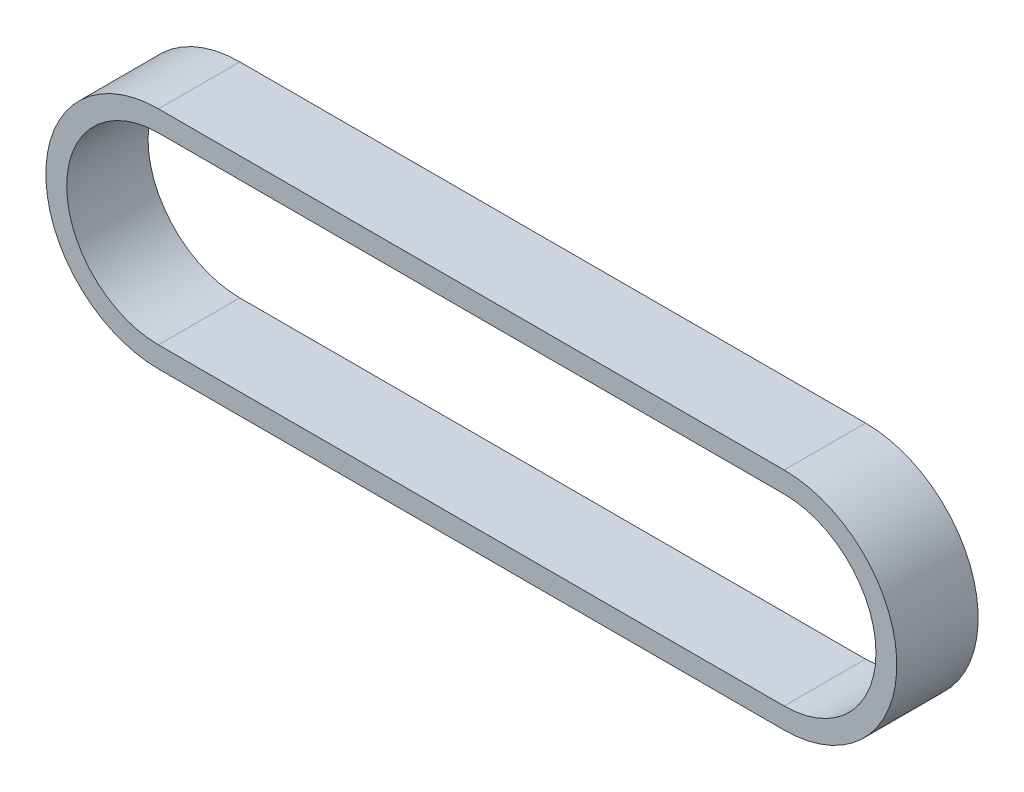
SolidWorks part; units mm, degrees
material "Rubber"
ref_plane "Front Plane" through (0, 0, 0) normal (0, 0, 1) x (1, 0, 0)
ref_plane "Top Plane" through (0, 0, 0) normal (0, 1, 0) x (1, 0, 0)
ref_plane "Right Plane" through (0, 0, 0) normal (1, 0, 0) x (0, 0, -1)
sketch "Sketch2" plane through (0, 0, 0) normal (0, 0, 1) x (1, 0, 0)
  line L0 (0, 0) -> (1, 0) construction
  line L1 (0, 0) -> (0, 1) construction
  line L2 (-0.0062, 44) -> (299.9938, 44.0423)
  line L3 (300.0062, -43.9577) -> (0.0062, -44)
  arc A0 (0.0062, -44) -> (-0.0062, 44) centre (0, 0) cw
  arc A1 (299.9938, 44.0423) -> (300.0062, -43.9577) centre (300, 0.0423) cw
extrude "Extrude-Thin1" add sketch "Sketch2" along normal mid plane 39 thin thin type one direction wall 10
